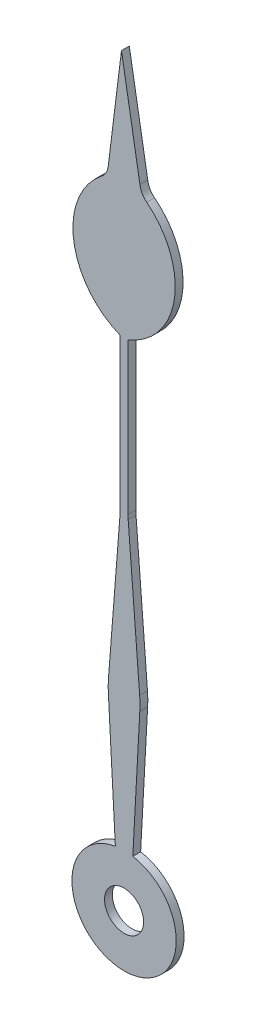
SolidWorks part; units mm, degrees
ref_plane "Front Plane" through (0, 0, 0) normal (0, 0, 1) x (1, 0, 0)
ref_plane "Top Plane" through (0, 0, 0) normal (0, 1, 0) x (1, 0, 0)
ref_plane "Right Plane" through (0, 0, 0) normal (1, 0, 0) x (0, 0, -1)
sketch "Sketch1" plane through (0, 0, 0) normal (0, 0, 1) x (1, 0, 0)
  line L0 (0, 0) -> (0, 18.2591) construction
  line L1 (-0.3343, 1.9719) -> (-0.603, 6.9199)
  line L2 (-0.5966, 7.4494) -> (-0.1561, 13.0677)
  line L3 (-0.15, 13.224) -> (-0.15, 19.0263)
  line L4 (-0.6072, 24.4146) -> (-0.1006, 28.506)
  line L5 (0.3343, 1.9719) -> (0.603, 6.9199)
  line L6 (0.5966, 7.4494) -> (0.1561, 13.0677)
  line L7 (0.15, 13.224) -> (0.15, 19.0263)
  line L8 (0.6072, 24.4146) -> (-0.1006, 28.506)
  circle A0 centre (0, 0) radius 0.75
  arc A1 (-0.3343, 1.9719) -> (0.3343, 1.9719) centre (0, 0) ccw
  arc A2 (-0.1561, 13.0677) -> (-0.15, 13.224) centre (-2.15, 13.224) ccw
  arc A3 (-0.603, 6.9199) -> (-0.5966, 7.4494) centre (3.3912, 7.1367) cw
  arc A4 (-0.15, 19.0263) -> (-0.8681, 23.9512) centre (0.9124, 21.696) cw
  arc A5 (-0.8681, 23.9512) -> (-0.6072, 24.4146) centre (-1.3019, 24.5006) ccw
  arc A6 (0.603, 6.9199) -> (0.5966, 7.4494) centre (-3.3912, 7.1367) ccw
  arc A7 (0.1561, 13.0677) -> (0.15, 13.224) centre (2.15, 13.224) cw
  arc A8 (0.8681, 23.9512) -> (0.6072, 24.4146) centre (1.3019, 24.5006) cw
  arc A9 (0.15, 19.0263) -> (0.8681, 23.9512) centre (-0.9124, 21.696) ccw
  dimension "D1" = 1.5
  dimension "D2" = 4
  dimension "D3" = 2
  dimension "D4" = 4
  dimension "D5" = 0.3
  dimension "D6" = 0.7
extrude "Boss-Extrude2" add sketch "Sketch1" along normal blind 0.3
